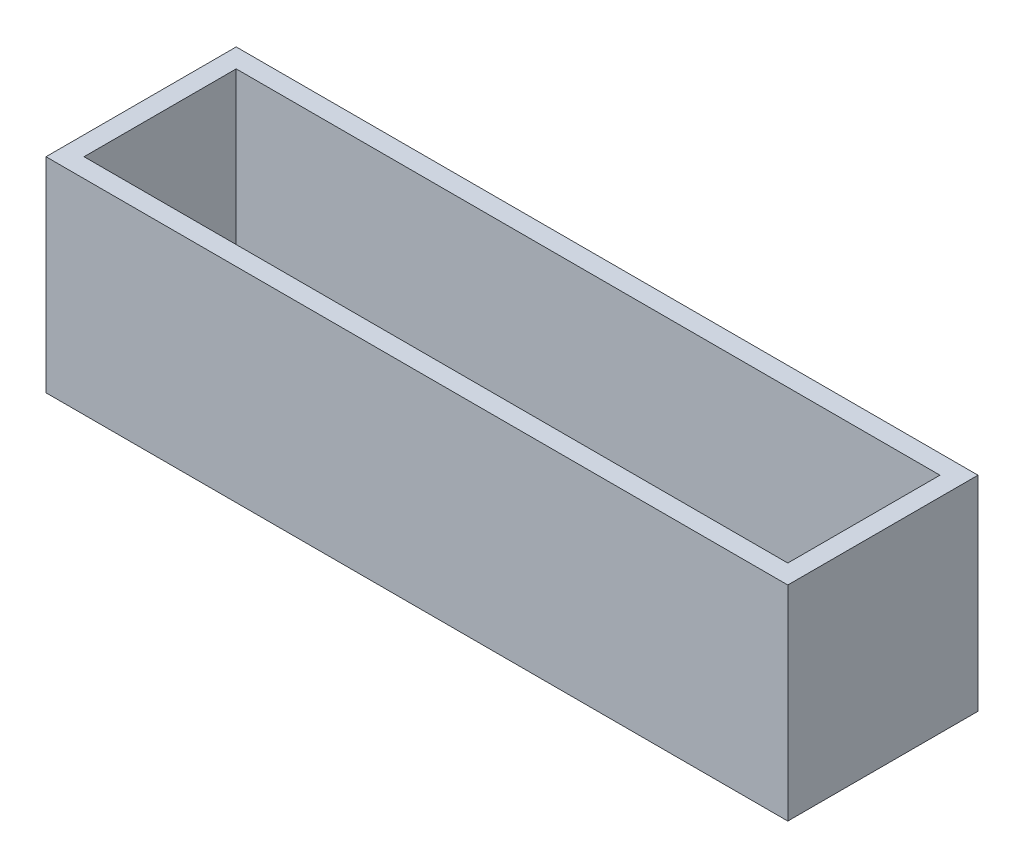
SolidWorks part; units mm, degrees
ref_plane "Front Plane" through (0, 0, 0) normal (0, 0, 1) x (1, 0, 0)
ref_plane "Top Plane" through (0, 0, 0) normal (0, 1, 0) x (1, 0, 0)
ref_plane "Right Plane" through (0, 0, 0) normal (1, 0, 0) x (0, 0, -1)
sketch "Эскиз1" plane through (0, 0, 0) normal (0, 1, 0) x (1, 0, 0)
  line L1 (-39, 10) -> (39, 10)
  line L2 (-39, 10) -> (-39, -10)
  line L3 (-39, -10) -> (39, -10)
  line L4 (39, 10) -> (39, -10)
  line L5 (-39, 10) -> (39, -10) construction
  line L6 (-39, -10) -> (39, 10) construction
  point P0 (0, 0)
  dimension "D1" = 78
  dimension "D2" = 20
extrude "Бобышка-Вытянуть1" add sketch "Эскиз1" along normal blind 21.5
shell "Оболочка1" thickness 2
